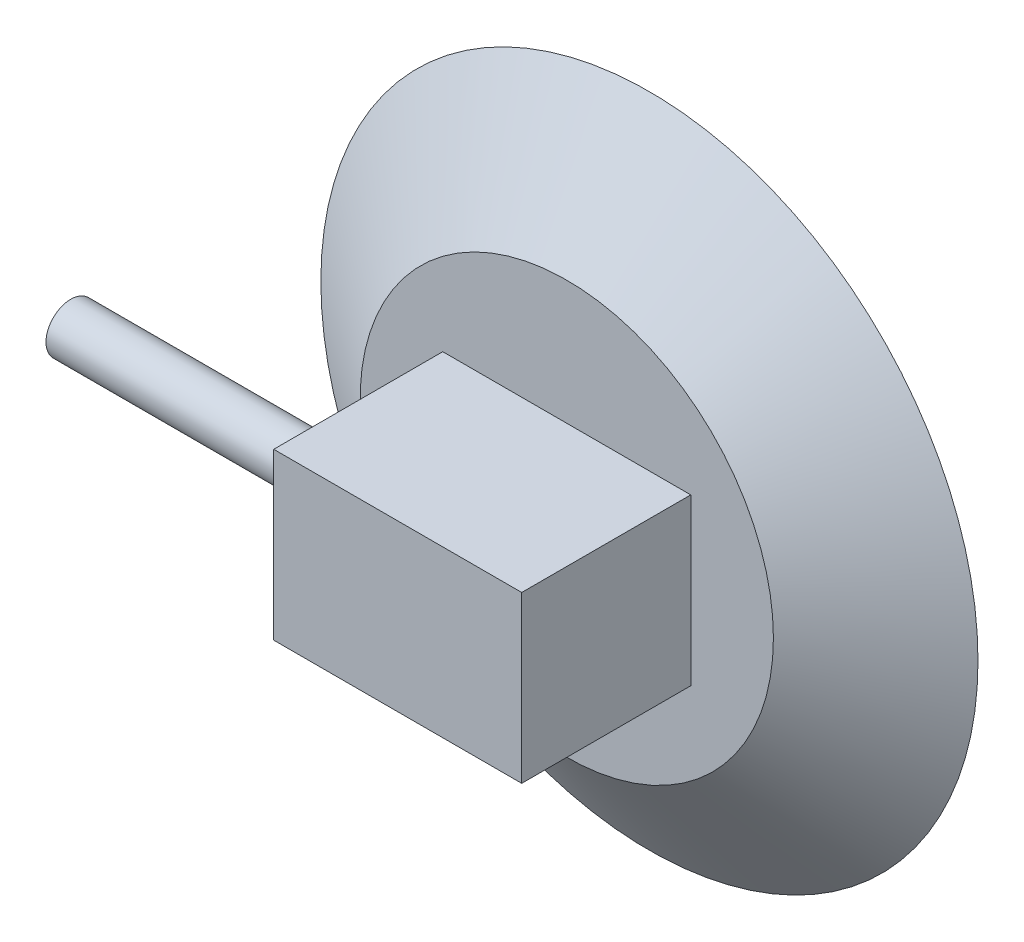
SolidWorks part; units mm, degrees
ref_plane "前视基准面" through (0, 0, 0) normal (0, 0, 1) x (1, 0, 0)
ref_plane "上视基准面" through (0, 0, 0) normal (0, 1, 0) x (1, 0, 0)
ref_plane "右视基准面" through (0, 0, 0) normal (1, 0, 0) x (0, 0, -1)
sketch "草图2" plane through (0, 0, 0) normal (0, 0, 1) x (1, 0, 0)
  circle A0 centre (0, 0) radius 79.5
  dimension "D1" = 159
ref_plane "基准面4" through (0, 0, 20) normal (0, 0, 1) x (1, 0, 0)
sketch "草图3" plane through (0, 0, 20) normal (0, 0, 1) x (1, 0, 0)
  circle A0 centre (0, 0) radius 50
  dimension "D1" = 100
loft "放样1" add profiles "草图2", "草图3"
sketch "草图4" plane through (0, 0, 20) normal (0, 0, 1) x (1, 0, 0)
  line L0 (0, 0) -> (0, -66.3516) construction
  line L1 (0, 0) -> (-87.6409, 0) construction
  line L3 (-30, 20) -> (30, 20)
  line L4 (-30, 20) -> (-30, -20)
  line L5 (-30, -20) -> (30, -20)
  line L6 (30, 20) -> (30, -20)
  dimension "D1" = 40
  dimension "D2" = 60
extrude "凸台-拉伸1" add sketch "草图4" along normal blind 40.9
sketch "草图5" plane through (-30, 0, 0) normal (-1, 0, 0) x (0, 0, 1)
  line L0 (20, 10) -> (40, 10)
  line L1 (20, -50) -> (20, 50) construction
  line L2 (20, 0) -> (77.0997, 0) construction
  line L3 (20, -10) -> (40, -10)
  line L4 (20, 10) -> (20, -10)
  arc A0 (40, -10) -> (40, 10) centre (40, 0) ccw
  dimension "D2" = 10
  dimension "D1" = 10
  dimension "D3" = 20
extrude "凸台-拉伸2" add sketch "草图5" along normal blind 10
sketch "草图6" plane through (-40, 0, 0) normal (-1, 0, 0) x (0, 0, 1)
  circle A0 centre (40, 0) radius 6
  dimension "D1" = 12
extrude "凸台-拉伸3" add sketch "草图6" along normal blind 60
